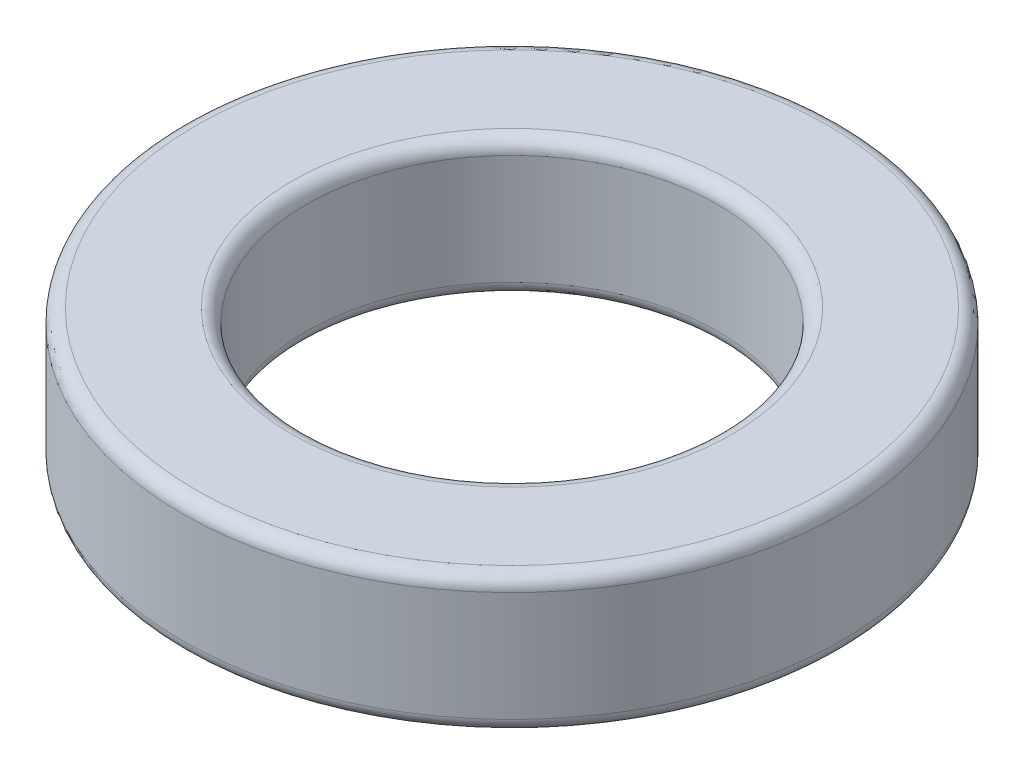
SolidWorks part; units mm, degrees
ref_plane "Front Plane" through (0, 0, 0) normal (0, 0, 1) x (1, 0, 0)
ref_plane "Top Plane" through (0, 0, 0) normal (0, 1, 0) x (1, 0, 0)
ref_plane "Right Plane" through (0, 0, 0) normal (1, 0, 0) x (0, 0, -1)
ref_plane "Plane1" through (0, 0, 0) normal (0, 0, -1) x (-1, 0, 0)
sketch "Sketch1" plane through (0, 0, 0) normal (0, 0, -1) x (-1, 0, 0)
  line L0 (-12, -0.5) -> (-12, -4.5)
  line L1 (-11.5, -5) -> (-8, -5)
  line L2 (-7.5, -4.5) -> (-7.5, -0.5)
  line L3 (-8, 0) -> (-11.5, 0)
  line L4 (0, -5) -> (0, 0) construction
  arc A0 (-11.5, 0) -> (-12, -0.5) centre (-11.5, -0.5) ccw
  arc A1 (-12, -4.5) -> (-11.5, -5) centre (-11.5, -4.5) ccw
  arc A2 (-8, -5) -> (-7.5, -4.5) centre (-8, -4.5) ccw
  arc A3 (-7.5, -0.5) -> (-8, 0) centre (-8, -0.5) ccw
revolve "Revolve1" add sketch "Sketch1" angle 360 about L4
